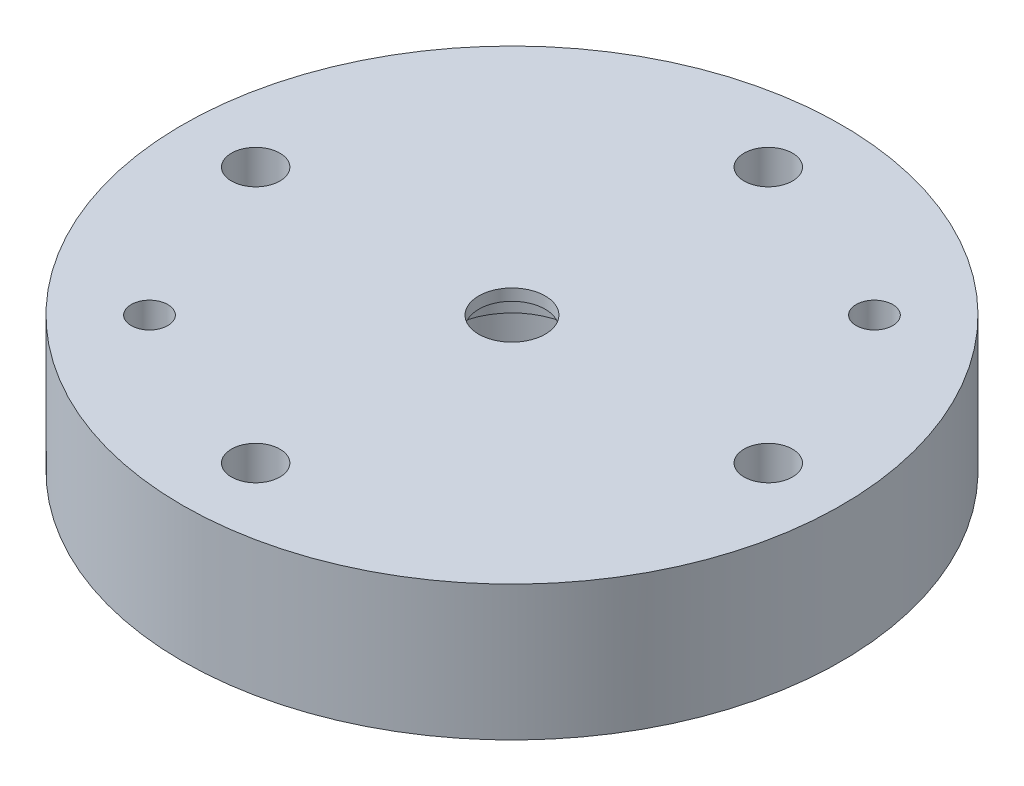
SolidWorks part; units mm, degrees
material "6061-T6 (SS)"
ref_plane "Front Plane" through (0, 0, 0) normal (0, 0, 1) x (1, 0, 0)
ref_plane "Top Plane" through (0, 0, 0) normal (0, 1, 0) x (1, 0, 0)
ref_plane "Right Plane" through (0, 0, 0) normal (1, 0, 0) x (0, 0, -1)
sketch "Sketch1" plane through (0, 0, 0) normal (0, 1, 0) x (1, 0, 0)
  circle A0 centre (0, 0) radius 57.15
  dimension "D1" = 114.3
extrude "seal seat hieght" add sketch "Sketch1" against normal blind 5.5372 contours A0
ref_plane "top end of seal" through (0, 0, 0) normal (0, 1, 0) x (1, 0, 0)
sketch "Sketch2" plane through (0, -5.5372, 0) normal (0, -1, 0) x (1, 0, 0)
  circle A1 centre (0, 0) radius 57.15
  circle A2 centre (0, 0) radius 57.15
  dimension "D1" = 0
extrude "seal diaphram hieght" add sketch "Sketch2" along normal blind 15.875
ref_plane "bottom end of seal" through (0, -21.4122, 0) normal (0, -1, 0) x (-1, 0, 0)
sketch "Sketch3" plane through (0, 0, 0) normal (0, 1, 0) x (1, 0, 0)
  circle A1 centre (0, 0) radius 57.15
  circle A2 centre (0, 0) radius 57.15
  dimension "D1" = 0
extrude "seal shoulder hieght" add sketch "Sketch3" along normal blind 2
sketch "Sketch4" plane through (0, -21.4122, 0) normal (0, -1, 0) x (1, 0, 0)
  circle A1 centre (0, 0) radius 57.15
  circle A2 centre (0, 0) radius 57.15
  dimension "D1" = 0
sketch "Sketch5" plane through (0, 0, 0) normal (0, 1, 0) x (1, 0, 0)
  circle A0 centre (0, 0) radius 11.1125
  dimension "D1" = 22.225
extrude "seal seat fit" cut sketch "Sketch5" against normal blind 5.5372
sketch "Sketch6" plane through (0, -21.4122, 0) normal (0, -1, 0) x (-1, 0, 0)
  circle A0 centre (0, 0) radius 12.7
  dimension "D1" = 25.4
sketch "Sketch7" plane through (0, 0, 0) normal (0, 1, 0) x (1, 0, 0)
  circle A0 centre (0, 0) radius 4.7625 construction
  circle A1 centre (0, 0) radius 5.7625
  dimension "D1" = 9.525
  dimension "D2" = 1
extrude "shaft clearance" cut sketch "Sketch7" along normal up to surface (2 mm away) up to face at (0, 2, 57.15)
sketch "bolt circle" plane through (0, 2, 0) normal (0, 1, 0) x (1, 0, 0)
  circle A0 centre (0, 0) radius 44.45 construction
  point P3 (-44.45, 0)
  point P4 (0, 44.45)
  point P5 (44.45, 0)
  point P6 (0, -44.45)
  dimension "D1" = 88.9
hole_wizard "M8 Clearance Hole1" positions "Sketch11" profile "Sketch12" hole size "M8" standard "ANSI Metric" end condition through all
sketch "Sketch11" plane through (0, 2, 0) normal (0, 1, 0) x (1, 0, 0)
  point P0 (-44.45, 0)
  point P3 (0, 44.45)
  point P6 (44.45, 0)
  point P9 (0, -44.45)
sketch "Sketch12" plane through (-44.45, 2, 0) normal (1, 0, 0) x (0, 0, 1)
  line L0 (0, 0) -> (0, 23.4122)
  line L1 (0, 23.4122) -> (4.2, 23.4122)
  line L2 (4.2, 23.4122) -> (4.2, 0)
  line L5 (4.2, 0) -> (0, 0)
  line L11 (0, -6.35) -> (0, 107.95) construction
  dimension "Thru Hole Dia." = 8.4
  dimension "Thru Hole Depth" = 23.4122
sketch "dowel hole positioning " plane through (0, 2, 0) normal (0, 1, 0) x (1, 0, 0)
  line L0 (0, 0) -> (53.8672, 0) construction
  line L1 (-31.4309, -31.4309) -> (31.4309, 31.4309) construction
  circle A0 centre (0, 0) radius 44.45 construction
  circle A1 centre (0, 0) radius 44.45 construction
  point P8 (0, 0)
  point P9 (31.4309, 31.4309)
  point P10 (-31.4309, -31.4309)
  dimension "D1" = 45
hole_wizard "1/4 (0.25) Press Dowel Hole1" positions "Sketch14" profile "Sketch15" hole size "1/4" standard "ANSI Inch" end condition through all
sketch "Sketch14" plane through (0, 2, 0) normal (0, 1, 0) x (1, 0, 0)
  point P0 (31.4309, 31.4309)
  point P3 (-31.4309, -31.4309)
sketch "Sketch15" plane through (31.4309, 2, -31.4309) normal (1, 0, 0) x (0, 0, 1)
  line L0 (0, 0) -> (0, 23.4122)
  line L1 (0, 23.4122) -> (3.175, 23.4122)
  line L2 (3.175, 23.4122) -> (3.175, 0)
  line L5 (3.175, 0) -> (0, 0)
  line L11 (0, -6.35) -> (0, 107.95) construction
  dimension "Thru Hole Dia." = 6.35
  dimension "Thru Hole Depth" = 23.4122
extrude "Cut-Extrude1" cut sketch "Sketch6" against normal up to surface (15.875 mm away) up to face at (0, -5.5372, 11.1125)
sketch "Sketch16" plane through (0, 2, 0) normal (0, 1, 0) x (1, 0, 0)
  line L1 (0, 0) -> (-140.97, 0)
  line L2 (0, 0) -> (0, 59.563)
  line L3 (0, 59.563) -> (-140.97, 59.563)
  line L5 (-140.97, 0) -> (-140.97, 59.563)
  dimension "D1" = 59.563
  dimension "D2" = 140.97
equation "\"seal seat height\"=5.5372"
equation "\"D1@seal seat hieght\" = \"seal seat height\""
equation "\"seal diaphram height\"=15.875"
equation "\"D1@seal diaphram hieght\" = \"seal diaphram height\""
equation "\"seal shoulder height\"=2"
equation "\"D1@seal shoulder hieght\" = \"seal shoulder height\""
equation "\"seal seat OD\"= .875in"
equation "\"D1@Sketch5\"=\"seal seat OD\""
equation "\"D1@seal seat fit\" = \"seal seat height\""
equation "\"seal diaphram clearance\"=25.4"
equation "\"D1@Sketch6\"=\"seal diaphram clearance\""
equation "\"seal ID\"=9.525"
equation "\"D1@Sketch7\"=\"seal ID\""
equation "\"bolt circle dia\"=88.9"
equation "\"D1@bolt circle\" = \"bolt circle dia\""
